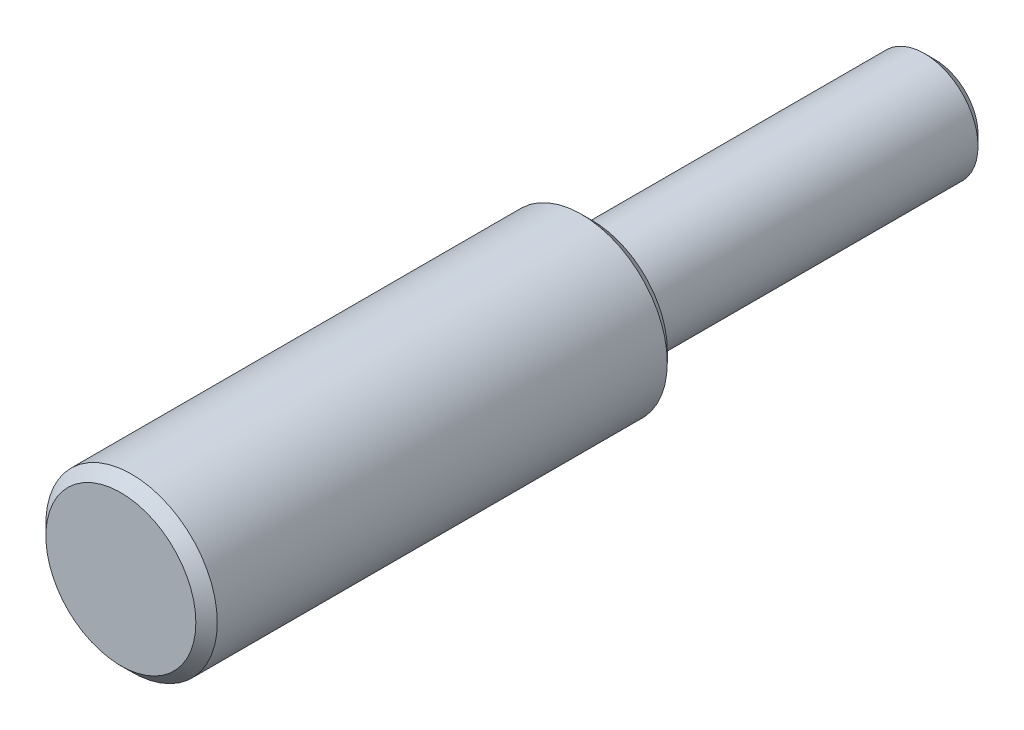
SolidWorks part; units mm, degrees
ref_plane "Front Plane" through (0, 0, 0) normal (0, 0, 1) x (1, 0, 0)
ref_plane "Top Plane" through (0, 0, 0) normal (0, 1, 0) x (1, 0, 0)
ref_plane "Right Plane" through (0, 0, 0) normal (1, 0, 0) x (0, 0, -1)
sketch "Sketch1" plane through (0, 0, 0) normal (0, 0, 1) x (1, 0, 0)
  circle A0 centre (0, 0) radius 2.5
  dimension "D1" = 5
extrude "Boss-Extrude1" add sketch "Sketch1" along normal blind 16
sketch "Sketch2" plane through (0, 0, 16) normal (0, 0, 1) x (1, 0, 0)
  circle A0 centre (0, 0) radius 4
  dimension "D1" = 8
extrude "Boss-Extrude2" add sketch "Sketch2" along normal blind 22
chamfer "Chamfer1" distance 0.5 angle 45 3 edges at (2.5, 0, 0) (4, 0, 38) (4, 0, 16)
fillet "Fillet1" radius 0.5 1 edges at (2.5, 0, 16)
